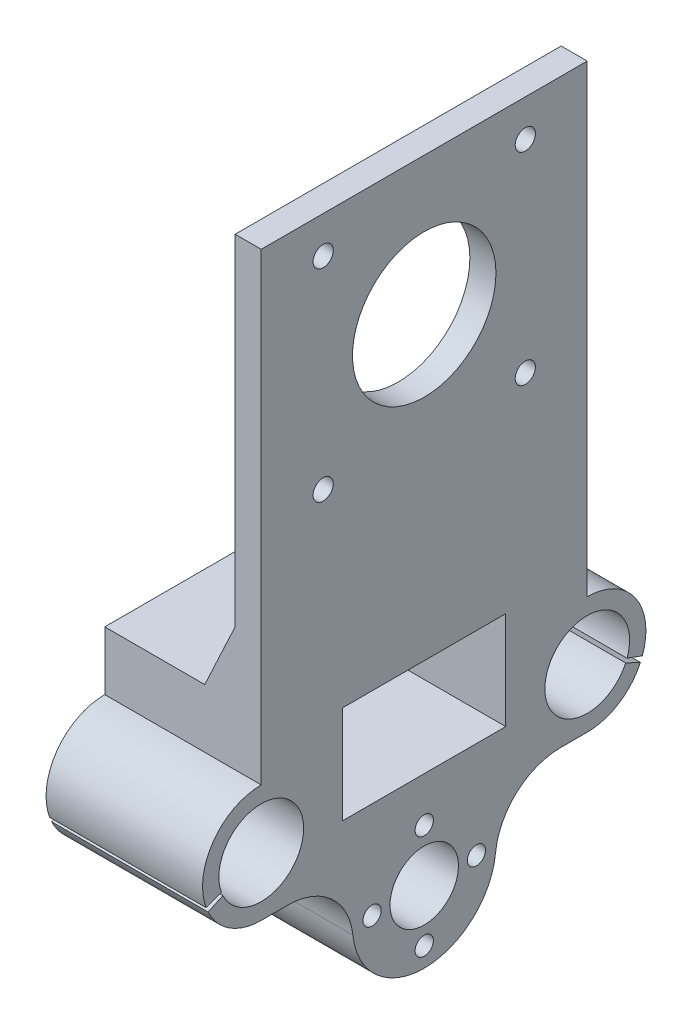
SolidWorks part; units mm, degrees
ref_plane "Front Plane" through (0, 0, 0) normal (0, 0, 1) x (1, 0, 0)
ref_plane "Top Plane" through (0, 0, 0) normal (0, 1, 0) x (1, 0, 0)
ref_plane "Right Plane" through (0, 0, 0) normal (1, 0, 0) x (0, 0, -1)
sketch "Sketch1" plane through (0, 0, 0) normal (1, 0, 0) x (0, 0, -1)
  line L0 (21.15, 33.075) -> (-21.15, -9.225) construction
  line L1 (-25, 33.075) -> (25, 33.075)
  line L2 (-25, 33.075) -> (-25, -33.075)
  line L3 (-25, -33.075) -> (25, -33.075)
  line L4 (25, 33.075) -> (25, -33.075)
  line L5 (0, -33.075) -> (0, 33.075) construction
  line L6 (-25, 0) -> (25, 0) construction
  line L7 (-21.15, 33.075) -> (21.15, 33.075) construction
  line L8 (-21.15, 33.075) -> (-21.15, -9.225) construction
  line L9 (-21.15, -9.225) -> (21.15, -9.225) construction
  line L10 (21.15, 33.075) -> (21.15, -9.225) construction
  line L11 (0, -9.225) -> (0, 33.075) construction
  line L12 (-21.15, 11.925) -> (21.15, 11.925) construction
  line L13 (-21.15, 33.075) -> (21.15, -9.225) construction
  circle A0 centre (0, 11.925) radius 11
  circle A1 centre (-15.5, 27.425) radius 1.55
  circle A2 centre (15.5, 27.425) radius 1.55
  circle A3 centre (15.5, -3.575) radius 1.55
  circle A4 centre (-15.5, -3.575) radius 1.55
  point P0 (0, 0)
  dimension "D3" = 22
  dimension "D6" = 3.1
  dimension "D1" = 50
  dimension "D2" = 45
  dimension "D4" = 42.3
  dimension "D5" = 31
extrude "Boss-Extrude1" add sketch "Sketch1" along normal blind 4
sketch "Sketch2" plane through (0, 0, 0) normal (-1, 0, 0) x (0, 0, 1)
  line L0 (25, 33.075) -> (25, -33.075) construction
  line L1 (-25, -33.075) -> (25, -33.075)
  line L2 (-25, -33.075) -> (-25, -29.075)
  line L3 (-25, -29.075) -> (25, -29.075)
  line L4 (25, -33.075) -> (25, -29.075)
  dimension "D1" = 4
extrude "Boss-Extrude2" add sketch "Sketch2" along normal blind 38
chamfer "Chamfer1" distance 10 angle 25 1 edges at (0, -29.075, 0)
sketch "Sketch3" plane through (-38, 0, 0) normal (-1, 0, 0) x (0, 0, 1)
  line L0 (-25, -33.075) -> (-25, -38.075)
  line L1 (-25, -47.075) -> (-25, -38.075) construction
  line L4 (-30.891, -49.822) -> (-33.1568, -50.8786)
  line L5 (-25, -33.075) -> (25, -33.075) construction
  line L6 (-25, -33.075) -> (25, -33.075)
  line L7 (0, -23.1) -> (0, 23.1) construction
  line L9 (-31.108, -49.2981) -> (-33.4572, -50.1532)
  line L10 (-25, -47.075) -> (-34, -47.075) construction
  line L11 (25, -47.075) -> (34, -47.075) construction
  line L12 (25, -47.075) -> (25, -38.075) construction
  line L13 (31.108, -49.2981) -> (33.4572, -50.1532)
  line L14 (30.891, -49.822) -> (33.1568, -50.8786)
  line L15 (25, -33.075) -> (25, -38.075)
  line L16 (25, -56.075) -> (7.7057, -56.075)
  line L17 (-7.7057, -56.075) -> (-25, -56.075)
  arc A0 (-25, -38.075) -> (-33.4572, -50.1532) centre (-25, -47.075) ccw
  arc A1 (-30.891, -49.822) -> (-31.108, -49.2981) centre (-25, -47.075) ccw
  arc A4 (-33.1568, -50.8786) -> (-25, -56.075) centre (-25, -47.075) ccw
  arc A5 (33.1568, -50.8786) -> (25, -56.075) centre (25, -47.075) cw
  arc A6 (30.891, -49.822) -> (31.108, -49.2981) centre (25, -47.075) cw
  arc A7 (25, -38.075) -> (33.4572, -50.1532) centre (25, -47.075) cw
  circle A8 centre (0, -63.925) radius 5.25
  circle A9 centre (0, -63.925) radius 8 construction
  circle A10 centre (0, -55.925) radius 1.4
  circle A11 centre (-8, -63.925) radius 1.4
  circle A12 centre (0, -71.925) radius 1.4
  circle A13 centre (8, -63.925) radius 1.4
  arc A14 (-7.7057, -56.075) -> (7.7057, -56.075) centre (0, -63.925) ccw
  dimension "D1" = 18
  dimension "D3" = 13
  dimension "D7" = 10.5
  dimension "D8" = 16
  dimension "D9" = 2.8
  dimension "D10" = 22
  dimension "D2" = 5
  dimension "D4" = 20
  dimension "D5" = 25
  dimension "D6" = 30.85
extrude "Boss-Extrude3" add sketch "Sketch3" against normal blind 24 from offset 18 offset against normal yes
sketch "Sketch4" plane through (0, -33.075, 0) normal (0, -1, 0) x (1, 0, 0)
  line L4 (-38, -25) -> (-20, -25)
  line L5 (-20, -25) -> (-20, 25)
  line L6 (-20, 25) -> (-38, 25)
  line L7 (-38, 25) -> (-38, -25)
  line L8 (-38, -25) -> (-20, -25)
  line L10 (-20, 25) -> (-38, 25)
  line L11 (-38, 25) -> (-38, -25)
  line L13 (-20, -25) -> (-20, 25)
  dimension "D1" = 0
extrude "Cut-Extrude1" cut sketch "Sketch4" against normal blind 24
fillet "Fillet1" radius 10 2 edges at (-8, -56.075, 7.7057) (-8, -56.075, -7.7057)
sketch "Sketch5" plane through (-20, 0, 0) normal (-1, 0, 0) x (0, 0, 1)
  line L0 (-25, -29.075) -> (25, -29.075) construction
  line L1 (12.5, -49.075) -> (-12.5, -49.075)
  line L2 (12.5, -49.075) -> (12.5, -34.075)
  line L3 (12.5, -34.075) -> (-12.5, -34.075)
  line L4 (-12.5, -49.075) -> (-12.5, -34.075)
  line L5 (0, -34.075) -> (0, -49.075) construction
  line L6 (12.5, -41.575) -> (-12.5, -41.575) construction
  line L7 (0, -23.1) -> (0, 23.1) construction
  point P0 (0, -41.575)
  dimension "D1" = 5
  dimension "D2" = 25
  dimension "D3" = 15
extrude "Cut-Extrude2" cut sketch "Sketch5" against normal through all
